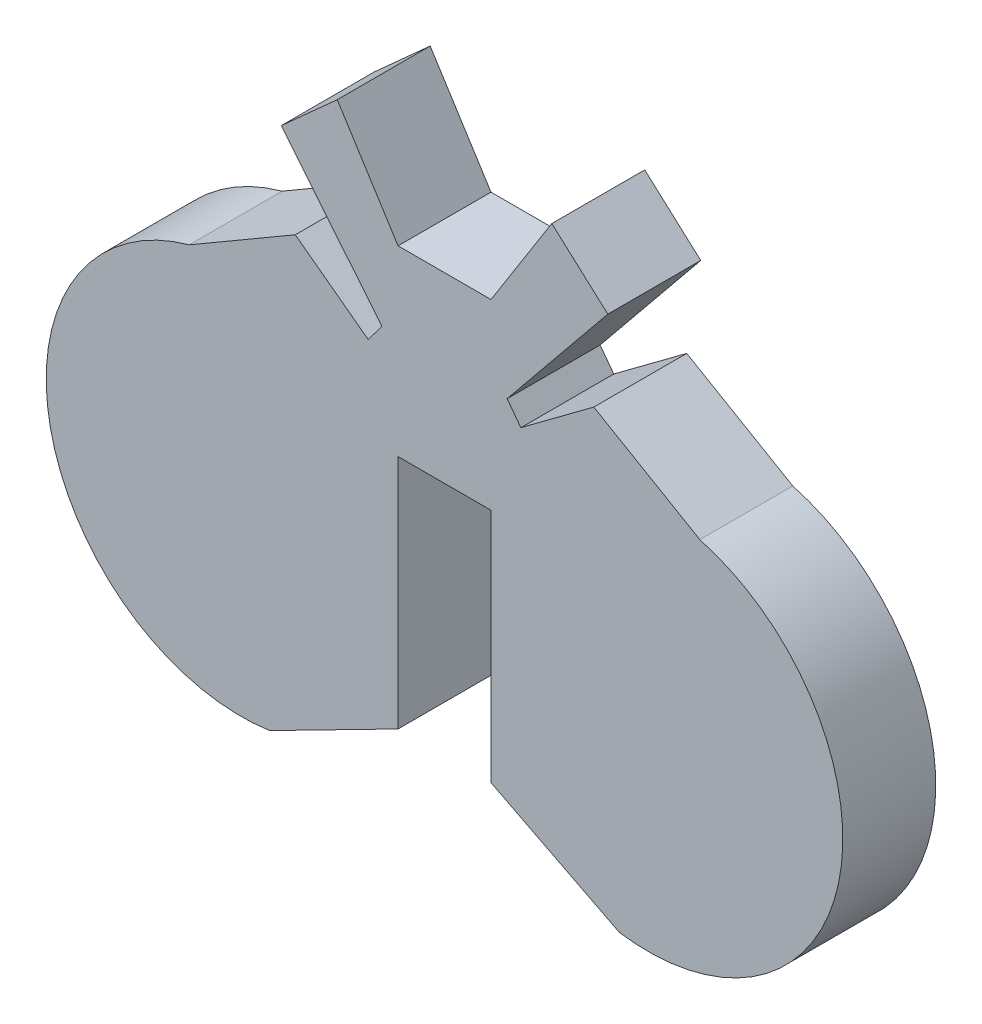
SolidWorks part; units mm, degrees
ref_plane "Front Plane" through (0, 0, 0) normal (0, 0, 1) x (1, 0, 0)
ref_plane "Top Plane" through (0, 0, 0) normal (0, 1, 0) x (1, 0, 0)
ref_plane "Right Plane" through (0, 0, 0) normal (1, 0, 0) x (0, 0, -1)
sketch "Sketch1" plane through (0, 0, 0) normal (0, 0, 1) x (1, 0, 0)
  line L0 (0, 0) -> (0, 6.891) construction
  line L1 (1.5, 6.891) -> (-1.5, 6.891)
  line L2 (-1.5, 6.891) -> (-3.4628, 9.9955)
  line L3 (-3.4628, 9.9955) -> (-5.2701, 8.3666)
  line L4 (-5.2701, 8.3666) -> (-2.0223, 4.3801)
  line L5 (-2.0223, 4.3801) -> (-2.4625, 3.789)
  line L6 (-2.4625, 3.789) -> (-4.8165, 5.5419)
  line L7 (-4.8165, 5.5419) -> (-8.2406, 3.5486)
  line L8 (1.5, 0) -> (-1.5, 0)
  line L9 (-1.5, 0) -> (-1.5, -6.614)
  line L10 (-1.5, -6.614) -> (-5.6427, -8.7304)
  line L11 (1.5, 0) -> (1.5, -6.614)
  line L12 (1.5, -6.614) -> (5.6427, -8.7304)
  line L13 (4.8165, 5.5419) -> (8.2406, 3.5486)
  line L14 (2.4625, 3.789) -> (4.8165, 5.5419)
  line L15 (2.0223, 4.3801) -> (2.4625, 3.789)
  line L16 (5.2701, 8.3666) -> (2.0223, 4.3801)
  line L17 (3.4628, 9.9955) -> (5.2701, 8.3666)
  line L18 (1.5, 6.891) -> (3.4628, 9.9955)
  arc A0 (-8.2406, 3.5486) -> (-5.6427, -8.7304) centre (-6.5689, -2.512) ccw
  arc A1 (8.2406, 3.5486) -> (5.6427, -8.7304) centre (6.5689, -2.512) cw
  dimension "D19" = 12.574
  dimension "D1" = 6.891
  dimension "D2" = 1.5
  dimension "D3" = 3.673
  dimension "D4" = 122.303
  dimension "D5" = 2.433
  dimension "D6" = 80.273
  dimension "D7" = 5.142
  dimension "D8" = 92.861
  dimension "D9" = 0.737
  dimension "D10" = 104.158
  dimension "D11" = 2.935
  dimension "D12" = 90
  dimension "D13" = 3.962
  dimension "D14" = 113.122
  dimension "D15" = 1.5
  dimension "D16" = 6.614
  dimension "D17" = 4.652
  dimension "D18" = 117.062
extrude "Boss-Extrude1" add sketch "Sketch1" against normal blind 3
sketch "Sketch2" plane through (0, 0, 0) normal (0, 0, 1) x (1, 0, 0)
  line L0 (-1.5, 0) -> (-1.5, 1)
  line L1 (-1.5, 1) -> (1.5, 1)
  line L2 (1.5, 1) -> (1.5, 0)
  line L3 (1.5, 0) -> (-1.5, 0)
  dimension "D1" = 1
extrude "Cut-Extrude1" cut sketch "Sketch2" against normal blind 10
